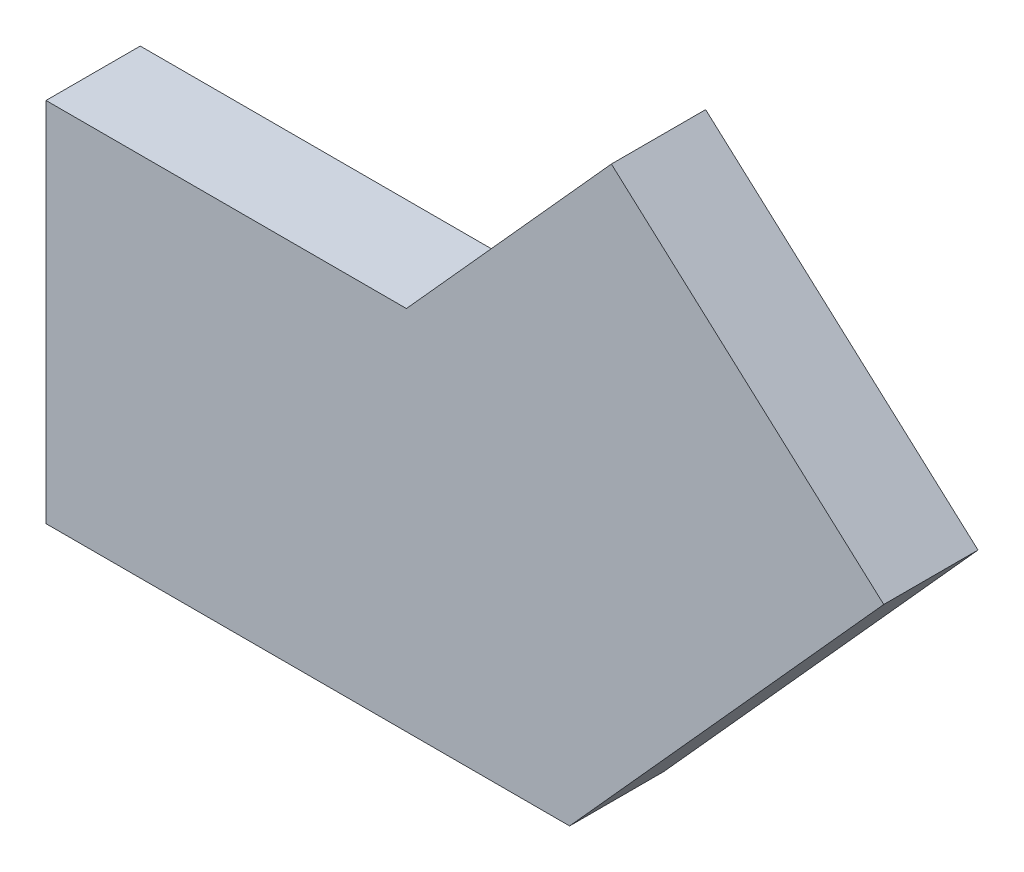
SolidWorks part; units mm, degrees
ref_plane "정면" through (0, 0, 0) normal (0, 0, 1) x (1, 0, 0)
ref_plane "윗면" through (0, 0, 0) normal (0, 1, 0) x (1, 0, 0)
ref_plane "우측면" through (0, 0, 0) normal (1, 0, 0) x (0, 0, -1)
sketch "Sketch1" plane through (0, 0, 0) normal (0, 0, 1) x (1, 0, 0)
  line L0 (0, 0) -> (50, 0)
  line L1 (50, 0) -> (80, 33.3184)
  line L2 (80, 33.3184) -> (53.9899, 56.7379)
  line L3 (53.9899, 56.7379) -> (34.417, 35)
  line L4 (34.417, 35) -> (0, 35)
  line L5 (0, 35) -> (0, 0)
  dimension "D1" = 50
  dimension "D2" = 80
  dimension "D3" = 132
  dimension "D4" = 35
  dimension "D5" = 35
extrude "Boss-Extrude1" add sketch "Sketch1" along normal blind 9 contours L4 L5 L0 L1 L2 L3
